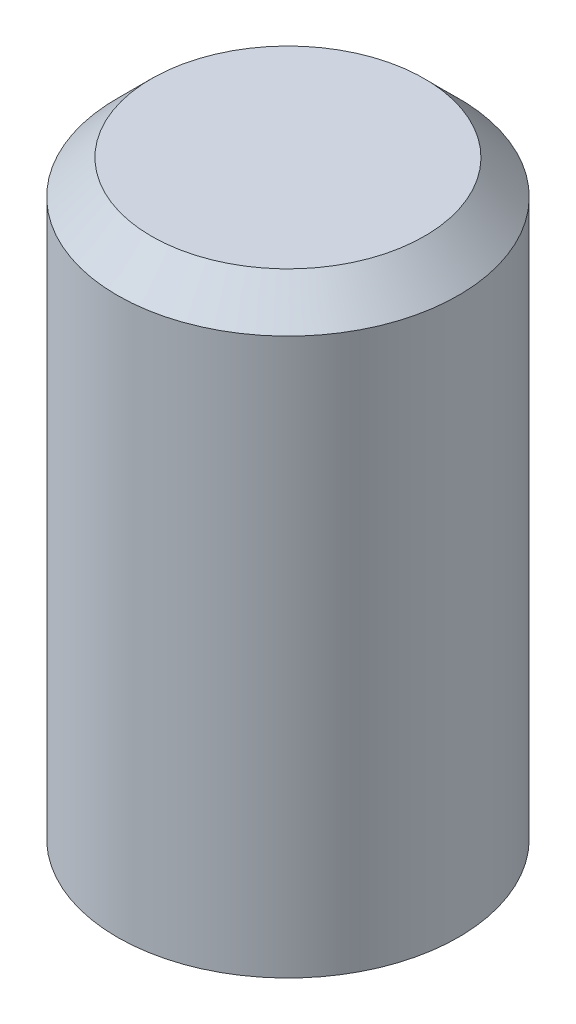
SolidWorks part; units mm, degrees
ref_plane "Спереди" through (0, 0, 0) normal (0, 0, 1) x (1, 0, 0)
ref_plane "Сверху" through (0, 0, 0) normal (0, 1, 0) x (1, 0, 0)
ref_plane "Справа" through (0, 0, 0) normal (1, 0, 0) x (0, 0, -1)
sketch "Эскиз1" plane through (0, 0, 0) normal (0, 1, 0) x (1, 0, 0)
  circle A0 centre (0, 0) radius 107
  dimension "D1" = 214
extrude "Бобышка-Вытянуть1" add sketch "Эскиз1" along normal blind 300 and the other way blind 70
chamfer "Фаска1" distance 21.4 angle 45 1 edges at (0, 300, 107)
ref_plane "face_for_horizont" through (0, -70, 0) normal (0, -1, 0) x (-1, 0, 0)
equation "\"H\"=70"
equation "\"D\"=214"
equation "\"L\"=300"
equation "\"D1@Эскиз1\" = \"D\""
equation "\"D1@Бобышка-Вытянуть1\" = \"L\""
equation "\"D2@Бобышка-Вытянуть1\" = \"H\""
equation "\"D1@Фаска1\" = \"D1@Эскиз1\"/10"
